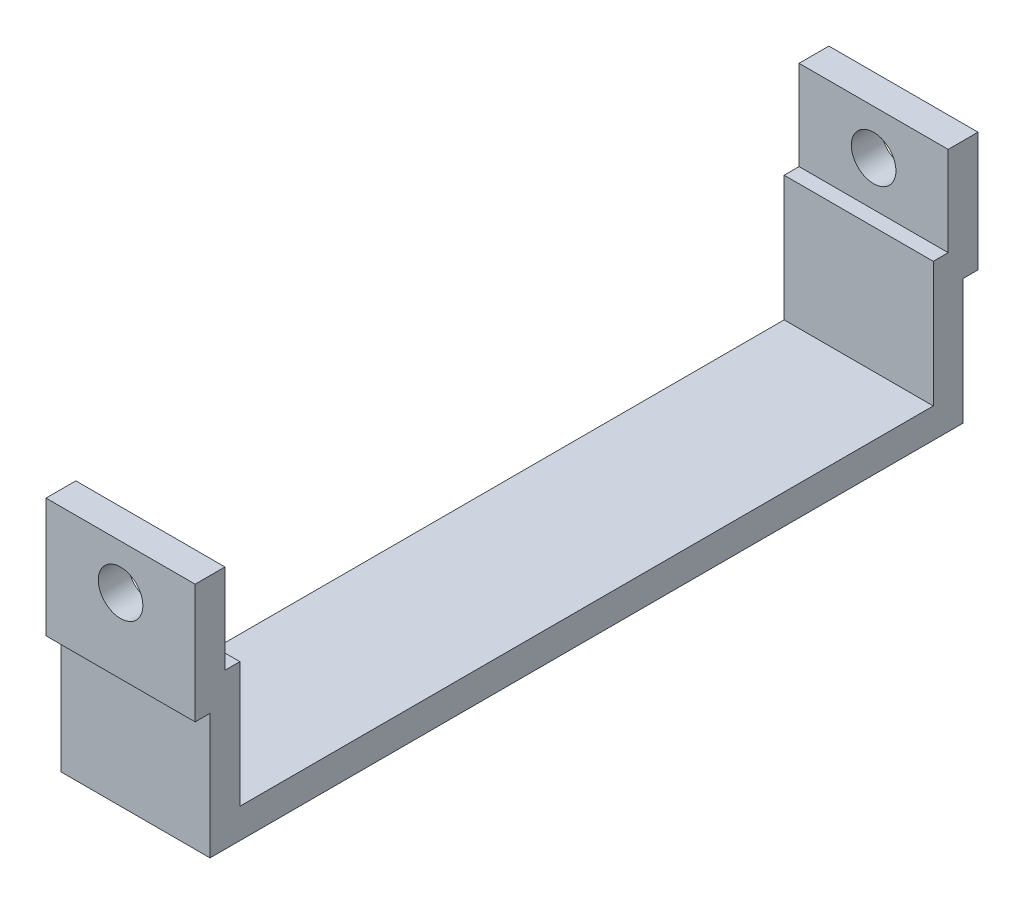
SolidWorks part; units mm, degrees
ref_plane "Front Plane" through (0, 0, 0) normal (0, 0, 1) x (1, 0, 0)
ref_plane "Top Plane" through (0, 0, 0) normal (0, 1, 0) x (1, 0, 0)
ref_plane "Right Plane" through (0, 0, 0) normal (1, 0, 0) x (0, 0, -1)
sketch "Sketch1" plane through (0, 0, 0) normal (1, 0, 0) x (0, 0, -1)
  line L0 (0, 0) -> (59.055, 0)
  line L1 (59.055, 0) -> (59.055, 10.668)
  line L2 (59.055, 10.668) -> (60.325, 10.668)
  line L3 (60.325, 10.668) -> (60.325, 18.288)
  line L4 (0, 0) -> (0, 10.668)
  line L5 (0, 10.668) -> (-1.27, 10.668)
  line L6 (-1.27, 10.668) -> (-1.27, 18.288)
  dimension "D1" = 59.055
  dimension "D2" = 10.668
  dimension "D3" = 7.62
  dimension "D4" = 1.27
  dimension "D5" = 1.27
  dimension "D6" = 10.668
extrude "Extrude-Thin1" add sketch "Sketch1" along normal blind 12.7 thin
hole_wizard "#6 Clearance Hole1" positions "Sketch3" profile "Sketch2" hole size "#6" standard "ANSI Inch"
sketch "Sketch3" plane through (0, 0, 1.27) normal (0, 0, -1) x (-1, 0, 0)
  line L0 (-12.7, 18.288) -> (0, 18.288) construction
  line L1 (0, 10.668) -> (0, 18.288) construction
  point P0 (-6.35, 14.478)
  dimension "D1" = 3.81
  dimension "D2" = 6.35
sketch "Sketch2" plane through (6.35, 14.478, 1.27) normal (1, 0, 0) x (0, 1, 0)
  line L0 (0, 0) -> (0, 8.7608)
  line L1 (0, 8.7608) -> (1.8986, 7.62)
  line L2 (1.8986, 7.62) -> (1.8986, 0)
  line L5 (1.8986, 0) -> (0, 0)
  line L10 (0, 8.7608) -> (-1.8986, 7.62) construction
  line L11 (0, -6.35) -> (0, 107.95) construction
  dimension "Hole Dia." = 3.7973
  dimension "Hole Depth" = 7.62
  dimension "Drill Angle" = 118
hole_wizard "#6 Clearance Hole2" positions "Sketch5" profile "Sketch4" hole size "#6" standard "ANSI Inch"
sketch "Sketch5" plane through (0, 0, -60.325) normal (0, 0, 1) x (1, 0, 0)
  line L0 (12.7, 18.288) -> (0, 18.288) construction
  line L1 (0, 18.288) -> (0, 10.668) construction
  point P0 (6.35, 14.478)
  dimension "D1" = 3.81
  dimension "D2" = 6.35
sketch "Sketch4" plane through (6.35, 14.478, -60.325) normal (1, 0, 0) x (0, -1, 0)
  line L0 (0, 0) -> (0, 8.7608)
  line L1 (0, 8.7608) -> (1.8986, 7.62)
  line L2 (1.8986, 7.62) -> (1.8986, 0)
  line L5 (1.8986, 0) -> (0, 0)
  line L10 (0, 8.7608) -> (-1.8986, 7.62) construction
  line L11 (0, -6.35) -> (0, 107.95) construction
  dimension "Hole Dia." = 3.7973
  dimension "Hole Depth" = 7.62
  dimension "Drill Angle" = 118
